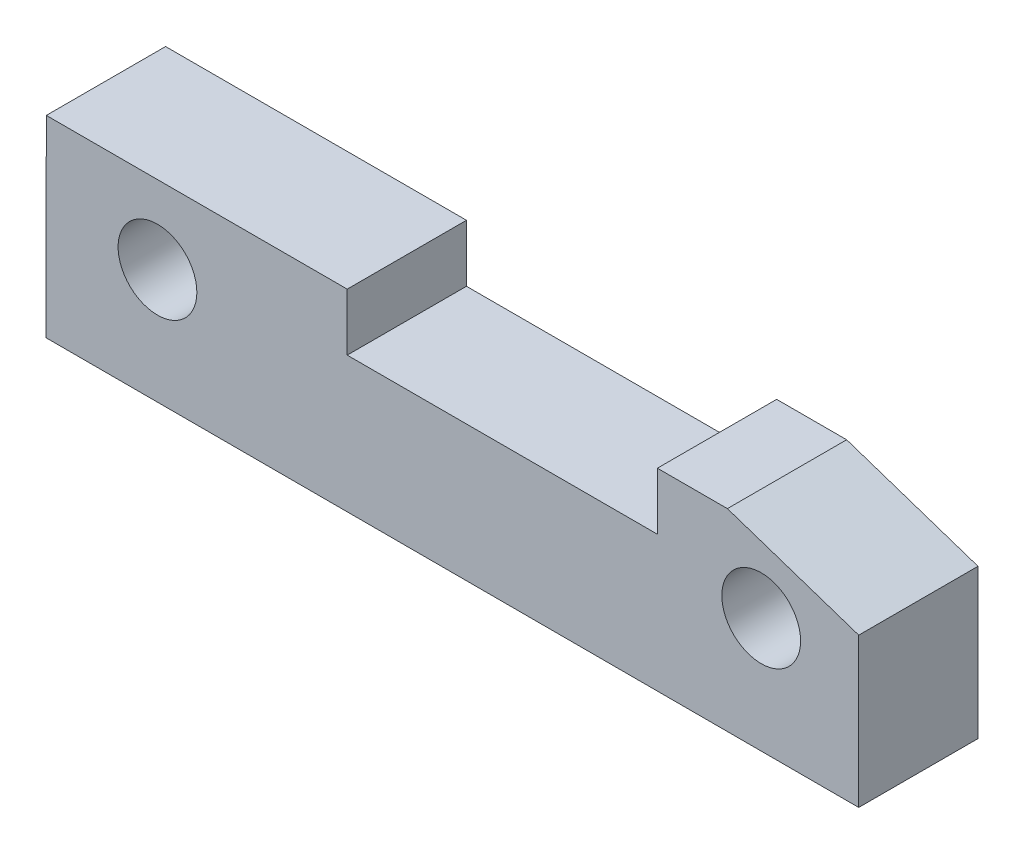
SolidWorks part; units mm, degrees
ref_plane "Front Plane" through (0, 0, 0) normal (0, 0, 1) x (1, 0, 0)
ref_plane "Top Plane" through (0, 0, 0) normal (0, 1, 0) x (1, 0, 0)
ref_plane "Right Plane" through (0, 0, 0) normal (1, 0, 0) x (0, 0, -1)
sketch "clamp outline" plane through (0, 0, 0) normal (0, 0, 1) x (1, 0, 0)
  line L0 (25.6309, 8.0798) -> (28.5658, 8.0798)
  line L1 (28.5658, 8.0798) -> (34.0717, 6.2395)
  line L2 (34.0717, 6.2395) -> (34.0717, -0.0175)
  line L3 (34.0717, -0.0175) -> (0.0129, -0.0175)
  line L4 (0.0129, -0.0175) -> (0.0129, 8.0798)
  line L5 (0.0129, 8.0798) -> (12.6274, 8.0798)
  line L6 (12.6274, 8.0798) -> (12.6274, 5.6827)
  line L7 (12.6274, 5.6827) -> (25.6309, 5.6827)
  line L8 (25.6309, 5.6827) -> (25.6309, 8.0798)
  spline S0 degree 3 poles (29.9831, 3.1585) (30.8947, 3.1585) (31.634, 3.8978) (31.634, 4.8094) (31.634, 5.721) (30.8947, 6.4603) (29.9831, 6.4603) knots 2 2 2 2 3 3 3 4 4 4 4
  spline S1 degree 3 poles (29.9831, 6.4603) (29.0712, 6.4603) (28.3322, 5.721) (28.3322, 4.8094) (28.3322, 3.8978) (29.0712, 3.1585) (29.9831, 3.1585) knots 0 0 0 0 1 1 1 2 2 2 2
  spline S2 degree 3 poles (6.3243, 4.8091) (6.3243, 3.8971) (5.5849, 3.1578) (4.6734, 3.1578) (3.7618, 3.1578) (3.0225, 3.8971) (3.0225, 4.8091) knots 2 2 2 2 3 3 3 4 4 4 4
  spline S3 degree 3 poles (3.0225, 4.8091) (3.0225, 5.721) (3.7618, 6.4603) (4.6734, 6.4603) (5.5849, 6.4603) (6.3243, 5.721) (6.3243, 4.8091) knots 0 0 0 0 1 1 1 2 2 2 2
sketch "outline" plane through (0, 0, 0) normal (0, 0, 1) x (1, 0, 0)
  line L0 (0.0129, 8.0798) -> (12.6274, 8.0798)
  line L1 (12.6274, 8.0798) -> (12.6274, 5.6827)
  line L2 (12.6274, 5.6827) -> (25.6309, 5.6827)
  line L3 (25.6309, 5.6827) -> (25.6309, 8.0798)
  line L4 (25.6309, 8.0798) -> (28.5658, 8.0798)
  line L5 (28.5658, 8.0798) -> (34.0717, 6.2395)
  line L6 (34.0717, 6.2395) -> (34.0717, -0.0175)
  line L7 (34.0717, -0.0175) -> (0, 0)
  line L8 (0, 0) -> (0.0129, 8.0798)
sketch "holes" plane through (0, 0, 0) normal (0, 0, 1) x (1, 0, 0)
  circle A0 centre (4.6734, 4.8091) radius 1.6509
  circle A1 centre (29.9831, 4.8094) radius 1.6509
extrude "Boss-Extrude1" add sketch "outline" against normal blind 5
extrude "Cut-Extrude1" cut sketch "holes" against normal through all
